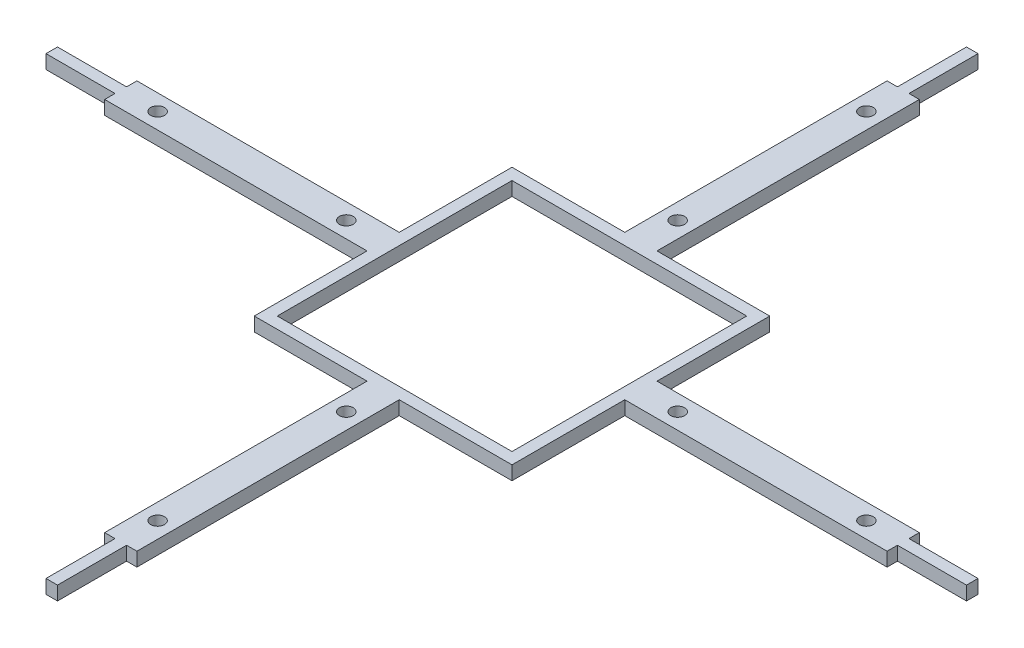
SolidWorks part; units mm, degrees
ref_plane "Front Plane" through (0, 0, 0) normal (0, 0, 1) x (1, 0, 0)
ref_plane "Top Plane" through (0, 0, 0) normal (0, 1, 0) x (1, 0, 0)
ref_plane "Right Plane" through (0, 0, 0) normal (1, 0, 0) x (0, 0, -1)
sketch "Sketch1" plane through (0, 0, 0) normal (0, 1, 0) x (1, 0, 0)
  line L0 (100, 3.5) -> (85, 3.5)
  line L1 (-28, -28) -> (28, -28)
  line L2 (-28, -28) -> (-28, 28)
  line L3 (-28, 28) -> (28, 28)
  line L4 (28, -28) -> (28, 28)
  line L5 (-28, -28) -> (28, 28) construction
  line L6 (-28, 28) -> (28, -28) construction
  line L7 (-25.5, -25.5) -> (25.5, -25.5)
  line L8 (-25.5, -25.5) -> (-25.5, 25.5)
  line L9 (-25.5, 25.5) -> (25.5, 25.5)
  line L10 (25.5, -25.5) -> (25.5, 25.5)
  line L11 (-25.5, -25.5) -> (25.5, 25.5) construction
  line L12 (-25.5, 25.5) -> (25.5, -25.5) construction
  line L13 (-3.5, -100) -> (3.5, -100)
  line L14 (-3.5, -100) -> (-3.5, 100)
  line L15 (-3.5, 100) -> (3.5, 100)
  line L16 (3.5, -100) -> (3.5, 100)
  line L17 (-3.5, -100) -> (3.5, 100) construction
  line L18 (-3.5, 100) -> (3.5, -100) construction
  line L19 (-100, -3.5) -> (100, -3.5)
  line L20 (-100, -3.5) -> (-100, 3.5)
  line L21 (-100, 3.5) -> (100, 3.5)
  line L22 (100, -3.5) -> (100, 3.5)
  line L23 (-100, -3.5) -> (100, 3.5) construction
  line L24 (-100, 3.5) -> (100, -3.5) construction
  line L25 (-3.5, 100) -> (-1.25, 100)
  line L26 (-3.5, 100) -> (-3.5, 85)
  line L27 (-3.5, 85) -> (-1.25, 85)
  line L28 (-1.25, 100) -> (-1.25, 85)
  line L29 (3.5, 100) -> (1.25, 100)
  line L30 (3.5, 100) -> (3.5, 85)
  line L31 (3.5, 85) -> (1.25, 85)
  line L32 (1.25, 100) -> (1.25, 85)
  line L33 (100, 3.5) -> (100, 1.25)
  line L34 (100, 1.25) -> (85, 1.25)
  line L35 (85, 3.5) -> (85, 1.25)
  line L36 (100, -3.5) -> (85, -3.5)
  line L37 (100, -3.5) -> (100, -1.25)
  line L38 (100, -1.25) -> (85, -1.25)
  line L39 (85, -3.5) -> (85, -1.25)
  line L40 (3.5, -100) -> (3.5, -85)
  line L41 (3.5, -100) -> (1.25, -100)
  line L42 (1.25, -100) -> (1.25, -85)
  line L43 (3.5, -85) -> (1.25, -85)
  line L44 (-3.5, -100) -> (-3.5, -85)
  line L45 (-3.5, -100) -> (-1.25, -100)
  line L46 (-1.25, -100) -> (-1.25, -85)
  line L47 (-3.5, -85) -> (-1.25, -85)
  line L48 (-100, -3.5) -> (-85, -3.5)
  line L49 (-100, -3.5) -> (-100, -1.25)
  line L50 (-100, -1.25) -> (-85, -1.25)
  line L51 (-85, -3.5) -> (-85, -1.25)
  line L52 (-100, 3.5) -> (-85, 3.5)
  line L53 (-100, 3.5) -> (-100, 1.25)
  line L54 (-100, 1.25) -> (-85, 1.25)
  line L55 (-85, 3.5) -> (-85, 1.25)
  line L56 (0, 100) -> (0, 102.7679) construction
  line L57 (0, 102.7679) -> (0, 15.8668) construction
  circle A0 centre (0, 77) radius 1.5
  circle A1 centre (0, 36) radius 1.5
  circle A2 centre (36, 0) radius 1.5
  circle A3 centre (77, 0) radius 1.5
  circle A4 centre (0, -36) radius 1.5
  circle A5 centre (0, -77) radius 1.5
  circle A6 centre (-36, 0) radius 1.5
  circle A7 centre (-77, 0) radius 1.5
  point P0 (0, 0)
  point P6 (0, 0)
  point P11 (0, 0)
  point P16 (0, 0)
  dimension "D14" = 3
  dimension "D15" = 3
  dimension "D1" = 56
  dimension "D2" = 56
  dimension "D3" = 51
  dimension "D4" = 51
  dimension "D5" = 200
  dimension "D6" = 7
  dimension "D7" = 200
  dimension "D8" = 7
  dimension "D9" = 15
  dimension "D10" = 15
  dimension "D11" = 2.5
  dimension "D12" = 2.25
  dimension "D13" = 2.25
  dimension "D16" = 4
  dimension "D17" = 8
  dimension "D18" = 8
extrude "Boss-Extrude1" add sketch "Sketch1" along normal blind 3 contours L32 L15 L28 L27 L14 L3 L16 L31 | L21 L55 L54 L20 L50 L51 L19 L2 | L19 L39 L38 L22 L34 L35 L21 L4 | L14 L47 L46 L13 L42 L43 L16 L1 | L21 L10 L19 L4 | L21 L2 L19 L8 | L9 L16 L3 L14 | L1 L16 L7 L14 | L19 L2 L1 L14 L7 L8 | L19 L10 L7 L16 L1 L4 | L10 L21 L4 L3 L16 L9 | L2 L21 L8 L9 L14 L3
